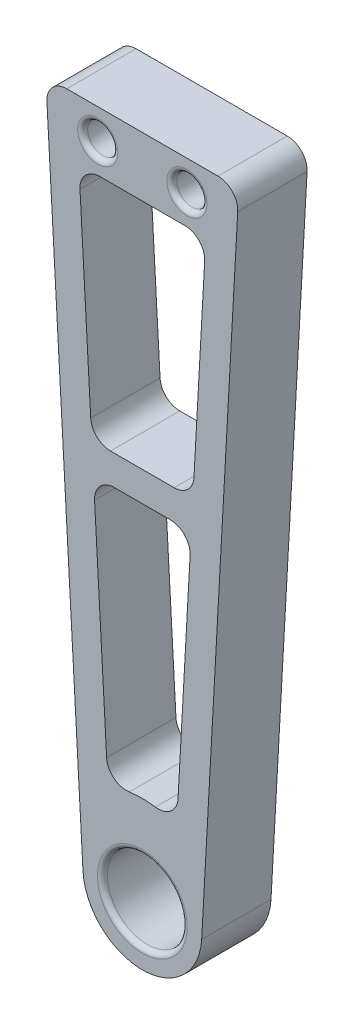
SolidWorks part; units mm, degrees
material "尼龙 101"
ref_plane "前视基准面" through (0, 0, 0) normal (0, 0, 1) x (1, 0, 0)
ref_plane "上视基准面" through (0, 0, 0) normal (0, 1, 0) x (1, 0, 0)
ref_plane "右视基准面" through (0, 0, 0) normal (1, 0, 0) x (0, 0, -1)
sketch "草图1" plane through (0, 0, 0) normal (0, 0, 1) x (1, 0, 0)
  line L0 (0, 0) -> (0, -90) construction
  line L1 (-10.983, -0.6111) -> (-5.9907, -90.3333)
  line L2 (10.983, -0.6111) -> (5.9907, -90.3333)
  line L3 (-7.4184, -10.6756) -> (-3.4668, -81.6945)
  line L4 (7.4184, -10.6756) -> (3.4668, -81.6945)
  circle A0 centre (0, 0) radius 11
  circle A1 centre (0, -90) radius 6
  circle A2 centre (0, 0) radius 5.5 construction
  circle A3 centre (5.5, 0) radius 1.01
  circle A4 centre (-2.75, -4.7631) radius 1.01
  circle A5 centre (-2.75, 4.7631) radius 1.01
  circle A6 centre (0, 0) radius 3.5
  circle A7 centre (0, -90) radius 4.025
  arc A8 (-7.4184, -10.6756) -> (7.4184, -10.6756) centre (0, 0) ccw
  arc A10 (3.4668, -81.6945) -> (-3.4668, -81.6945) centre (0, -90) ccw
  point P14 (0, 0)
  dimension "D1" = 22
  dimension "D2" = 11
  dimension "D3" = 2.02
  dimension "D5" = 7
  dimension "D6" = 12
  dimension "D7" = 8.05
  dimension "D10" = 2
  dimension "D11" = 9
  dimension "D8" = 90
  dimension "D9" = 3
  dimension "D4" = 3
extrude "凸台-拉伸1" add sketch "草图1" along normal blind 7 contours A1 L2 A0 L1 L4 A10 L3 A8 | A0 A6 A5 A4 A3 | A1 A7
sketch "草图2" plane through (0, 0, 7) normal (0, 0, 1) x (1, 0, 0)
  line L0 (-6.7452, -22.7747) -> (6.7452, -22.7747)
  line L1 (-7.4184, -10.6756) -> (-3.4668, -81.6945) construction
  line L2 (7.4184, -10.6756) -> (3.4668, -81.6945) construction
  line L3 (-6.4113, -28.7747) -> (6.4113, -28.7747)
  line L4 (0, 0) -> (0, -50000) construction
  line L5 (-6.7452, -22.7747) -> (-6.4113, -28.7747)
  line L6 (6.7452, -22.7747) -> (6.4113, -28.7747)
  circle A0 centre (-4.5, -25.7747) radius 1.525
  circle A2 centre (4.5, -25.7747) radius 1.525
  dimension "D1" = 3.05
  dimension "D3" = 3
  dimension "D2" = 9
  dimension "D4" = 3
extrude "凸台-拉伸2" add sketch "草图2" against normal up to surface (7 mm away) up to face at (0, -43.9861, 0)
sketch "草图3" plane through (0, 0, 7) normal (0, 0, 1) x (1, 0, 0)
  line L0 (-12.1126, -22.7747) -> (12.4405, -22.7747)
  line L1 (12.4405, -22.7747) -> (12.4405, 13.8022)
  line L2 (12.4405, 13.8022) -> (-12.1126, 13.8022)
  line L3 (-12.1126, 13.8022) -> (-12.1126, -22.7747)
extrude "切除-拉伸1" cut sketch "草图3" against normal blind 29
sketch "草图4" plane through (0, 0, 7) normal (0, 0, 1) x (1, 0, 0)
  line L0 (-5.106, -52.2346) -> (5.106, -52.2346)
  line L1 (-6.4113, -28.7747) -> (-3.4668, -81.6945) construction
  line L2 (6.4113, -28.7747) -> (3.4668, -81.6945) construction
  line L3 (-4.939, -55.2346) -> (4.939, -55.2346)
  line L4 (-5.106, -52.2346) -> (-4.939, -55.2346)
  line L5 (5.106, -52.2346) -> (4.939, -55.2346)
  dimension "D1" = 3
extrude "凸台-拉伸3" add sketch "草图4" against normal up to surface (7 mm away) up to face at (0, -55.061, 0)
fillet "圆角1" radius 2 10 edges at (-3.4668, -81.6945, 3.5) (3.4668, -81.6945, 3.5) (-6.4113, -28.7747, 3.5) (6.4113, -28.7747, 3.5) (9.7498, -22.7747, 3.5) (-9.7498, -22.7747, 3.5) (4.939, -55.2346, 3.5) (-4.939, -55.2346, 3.5) (5.106, -52.2346, 3.5) (-5.106, -52.2346, 3.5)
fillet "圆角2" radius 0.5 6 edges at (4.025, -90, 0) (-2.975, -25.7747, 0) (6.025, -25.7747, 0) (2.975, -25.7747, 7) (-2.975, -25.7747, 7) (4.025, -90, 7)
